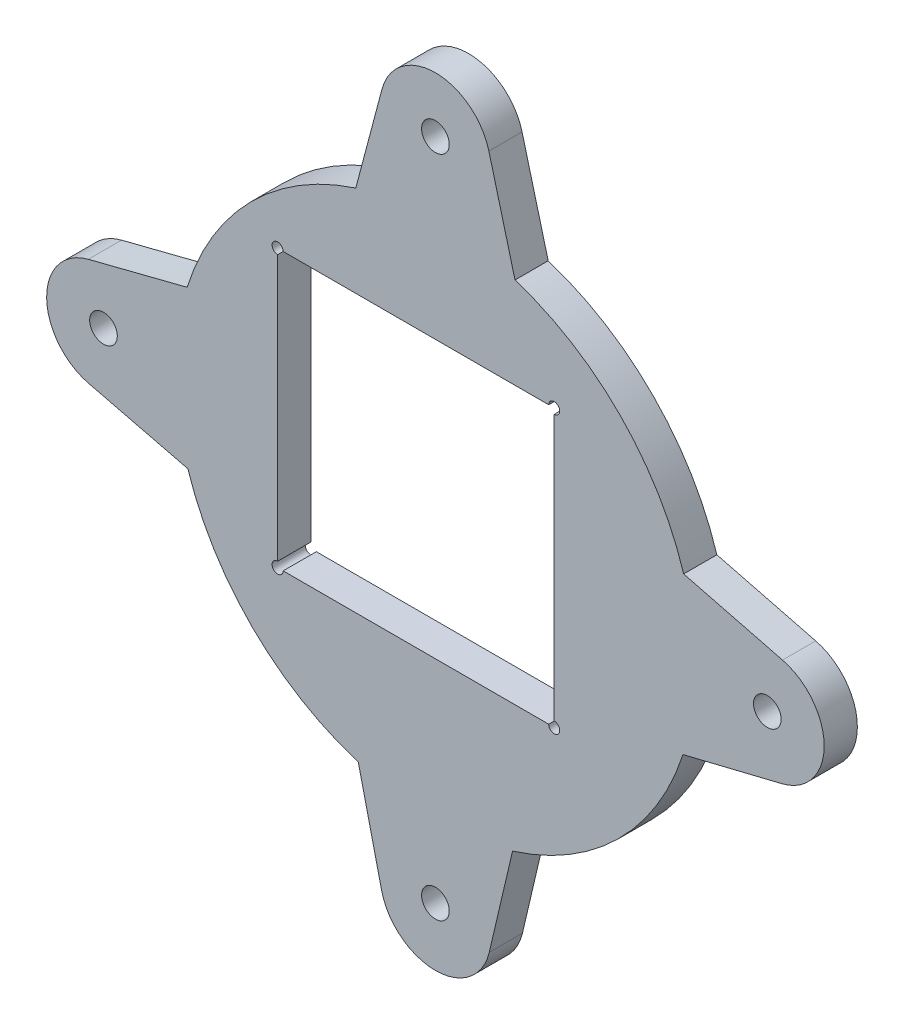
SolidWorks part; units mm, degrees
material "ABS PC"
ref_plane "Front Plane" through (0, 0, 0) normal (0, 0, 1) x (1, 0, 0)
ref_plane "Top Plane" through (0, 0, 0) normal (0, 1, 0) x (1, 0, 0)
ref_plane "Right Plane" through (0, 0, 0) normal (1, 0, 0) x (0, 0, -1)
sketch "Sketch1" plane through (0, 0, 0) normal (0, 0, 1) x (1, 0, 0)
  line L0 (-1.851, -4.2338) -> (-1.851, 25.7662) construction
  line L1 (-33.2216, 0.4748) -> (-24.2894, 2.7495)
  line L2 (-16.1131, -15.1084) -> (8.8869, -15.1084)
  line L3 (-16.1131, -15.1084) -> (-16.1131, 9.8916)
  line L4 (-16.1131, 9.8916) -> (8.8869, 9.8916)
  line L5 (8.8869, -15.1084) -> (8.8869, 9.8916)
  line L6 (-16.1131, -15.1084) -> (8.8869, 9.8916) construction
  line L7 (-16.1131, 9.8916) -> (8.8869, -15.1084) construction
  line L8 (-33.1776, -9.2269) -> (-24.2252, -11.4204)
  line L9 (-6.7189, -35.6491) -> (-8.8239, -26.6755)
  line L10 (3.0169, -35.6491) -> (5.1219, -26.6755)
  line L11 (29.4756, -9.2269) -> (20.5232, -11.4204)
  line L12 (29.5196, 0.4748) -> (20.5874, 2.7495)
  line L13 (-6.6841, 27.0473) -> (-9.0458, 18.1377)
  line L14 (2.9821, 27.0473) -> (5.3438, 18.1377)
  circle A0 centre (-1.851, 25.7662) radius 1.25
  circle A1 centre (28.149, -4.2338) radius 1.25
  circle A2 centre (-1.851, -34.2338) radius 1.25
  circle A3 centre (-31.851, -4.2338) radius 1.25
  circle A4 centre (-1.851, 25.7662) radius 5 construction
  circle A5 centre (-1.851, -4.2338) radius 23.5 construction
  circle A6 centre (28.2857, -4.3705) radius 5 construction
  circle A7 centre (-1.851, -34.5072) radius 5 construction
  circle A8 centre (-31.9877, -4.3705) radius 5 construction
  arc A9 (-6.6841, 27.0473) -> (2.9821, 27.0473) centre (-1.851, 25.7662) cw
  arc A10 (29.5196, 0.4748) -> (29.4756, -9.2269) centre (28.2857, -4.3705) cw
  arc A11 (3.0169, -35.6491) -> (-6.7189, -35.6491) centre (-1.851, -34.5072) cw
  arc A12 (-33.1776, -9.2269) -> (-33.2216, 0.4748) centre (-31.9877, -4.3705) cw
  arc A13 (-24.2894, 2.7495) -> (-9.0458, 18.1377) centre (-1.851, -4.2338) cw
  arc A14 (5.3438, 18.1377) -> (20.5874, 2.7495) centre (-1.851, -4.2338) cw
  arc A15 (20.5232, -11.4204) -> (5.1219, -26.6755) centre (-1.851, -4.2338) cw
  arc A16 (-8.8239, -26.6755) -> (-24.2252, -11.4204) centre (-1.851, -4.2338) cw
  point P25 (-1.851, -4.3705)
  dimension "D5" = 10
  dimension "D6" = 47
  dimension "D7" = 2.5
  dimension "D2" = 30
  dimension "D3" = 25
  dimension "D4" = 4
  dimension "D1" = 4
extrude "Boss-Extrude1" add sketch "Sketch1" along normal blind 3
sketch "Sketch2" plane through (0, 0, 3) normal (0, 0, 1) x (1, 0, 0)
  circle A0 centre (-16.1131, 9.8916) radius 0.5
  circle A1 centre (8.8869, 9.8916) radius 0.5
  circle A2 centre (8.8869, -15.1084) radius 0.5
  circle A3 centre (-16.1131, -15.1084) radius 0.5
  point P7 (8.8869, -15.1084)
  point P8 (8.8869, 9.8916)
  point P12 (9.2575, 9.8916)
  dimension "D1" = 1
extrude "Cut-Extrude1" cut sketch "Sketch2" against normal blind 10
